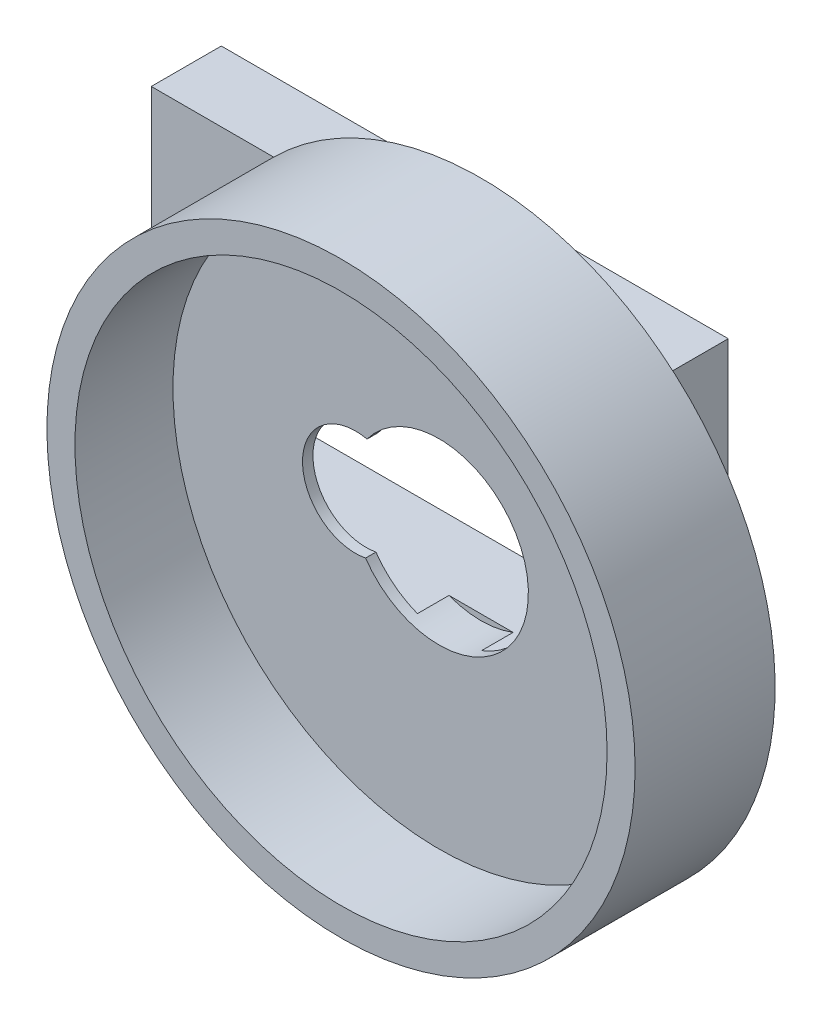
SolidWorks part; units mm, degrees
material "ABS"
ref_plane "Plan de face" through (0, 0, 0) normal (0, 0, 1) x (1, 0, 0)
ref_plane "Plan de dessus" through (0, 0, 0) normal (0, 1, 0) x (1, 0, 0)
ref_plane "Plan de droite" through (0, 0, 0) normal (1, 0, 0) x (0, 0, -1)
sketch "Esquisse1" plane through (0, 0, 0) normal (0, 0, 1) x (1, 0, 0)
  line L1 (-13, -0.5) -> (23.2, -0.5)
  line L2 (-13, -0.5) -> (-13, -30)
  line L3 (-13, -30) -> (23.2, -30)
  line L4 (23.2, -0.5) -> (23.2, -30)
sketch "Esquisse2" plane through (0, 0, 0) normal (0, 0, 1) x (1, 0, 0)
  line L1 (21.05, -8.973) -> (-12.003, -8.973)
  line L2 (21.05, -8.973) -> (21.05, -21.345)
  line L3 (21.05, -21.345) -> (-12.003, -21.345)
  line L4 (-12.003, -8.973) -> (-12.003, -21.345)
sketch "Esquisse3" plane through (0, 0, 0) normal (0, 0, 1) x (1, 0, 0)
  line L0 (21.05, -21.345) -> (-12.003, -21.345) construction
  line L1 (21.05, -8.973) -> (16.4916, -8.973)
  line L2 (21.05, -8.973) -> (21.05, -21.345)
  line L3 (21.05, -21.345) -> (16.4916, -21.345)
  line L4 (16.4916, -8.973) -> (16.4916, -21.345)
  line L6 (-12.003, -8.973) -> (-7.003, -8.973)
  line L7 (-12.003, -8.973) -> (-12.003, -21.353)
  line L8 (-12.003, -21.353) -> (-7.003, -21.353)
  line L9 (-7.003, -8.973) -> (-7.003, -21.353)
sketch "Esquisse4" plane through (0, 0, 0) normal (0, 0, 1) x (1, 0, 0)
  arc A0 (5.2992, -19.0172) -> (5.4087, -11.6055) centre (10.5484, -15.3881) ccw
  arc A1 (5.4087, -11.6055) -> (5.2992, -19.0172) centre (4.5853, -15.3) ccw
  circle A2 centre (10.5484, -15.3881) radius 12.3981
extrude "Boss.-Extru.1" add sketch "Esquisse1" along normal blind 5
extrude "Enlèv. mat.-Extru.1" cut sketch "Esquisse2" along normal blind 5
extrude "Boss.-Extru.2" add sketch "Esquisse3" against normal blind 3.5 from offset 5
extrude "Boss.-Extru.5" add sketch "Esquisse4" along normal blind 2 and the other way blind 1 from offset 6
sketch "Esquisse6" plane through (-13, 0, 0) normal (-1, 0, 0) x (0, 0, 1)
  line L1 (5, -8.973) -> (7.2565, -8.973)
  line L2 (5, -8.973) -> (5, -21.345)
  line L3 (5, -21.345) -> (7.2565, -21.345)
  line L4 (7.2565, -8.973) -> (7.2565, -21.345)
extrude "Enlèv. mat.-Extru.3" cut sketch "Esquisse6" against normal up to surface (29.4916 mm away) up to face at (16.4916, -15.2354, 3.8333)
sketch "Sketch4" plane through (0, 0, 5) normal (0, 0, 1) x (1, 0, 0)
  line L0 (-1.8497, -15.3881) -> (22.9466, -15.3881) construction
  circle A0 centre (10.5484, -15.3881) radius 12.3981 construction
  circle A1 centre (10.5484, -15.3881) radius 21
  circle A2 centre (10.5484, -15.3881) radius 19
  dimension "D1" = 38
  dimension "D2" = 42
extrude "Boss-Extrude2" add sketch "Sketch4" along normal blind 10
sketch "Sketch5" plane through (0, 0, 8) normal (0, 0, 1) x (1, 0, 0)
  line L0 (10.5484, -15.3881) -> (29.5484, -15.3881) construction
  line L1 (29.5484, -15.3881) -> (-8.4516, -15.3881) construction
  circle A0 centre (10.5484, -15.3881) radius 19 construction
  arc A1 (-7.003, -8.1116) -> (-7.003, -22.6646) centre (10.5484, -15.3881) ccw construction
  circle A2 centre (10.5484, -15.3881) radius 12.35
  circle A3 centre (10.5484, -15.3881) radius 20
  dimension "D1" = 24.7
  dimension "D2" = 40
extrude "Boss-Extrude7" add sketch "Sketch5" against normal blind 0.75
